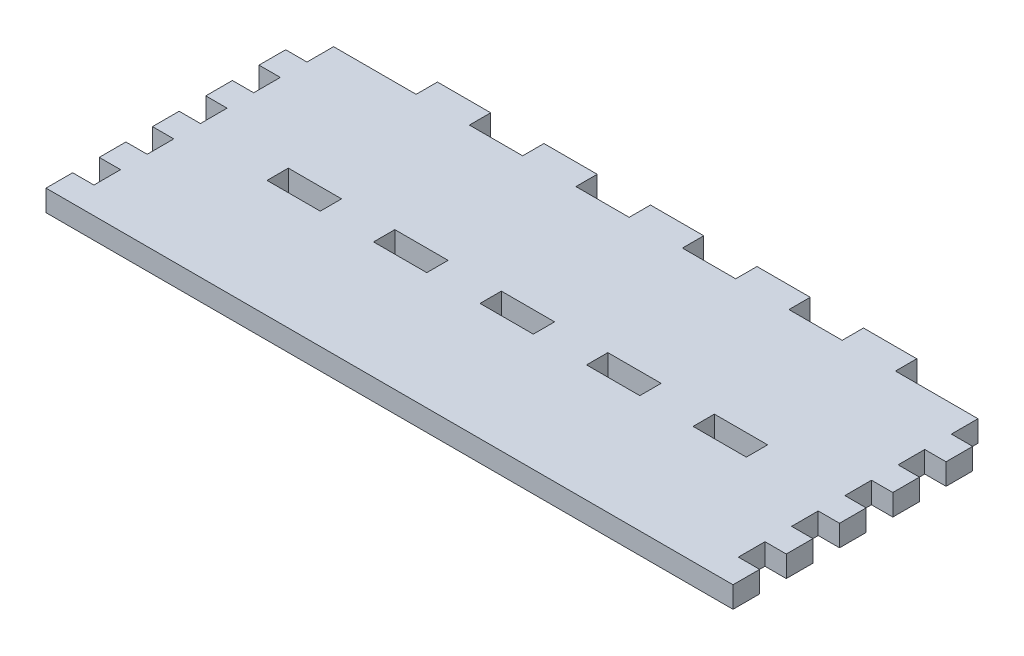
SolidWorks part; units mm, degrees
material "Maple"
ref_plane "Front Plane" through (0, 0, 0) normal (0, 0, 1) x (1, 0, 0)
ref_plane "Top Plane" through (0, 0, 0) normal (0, 1, 0) x (1, 0, 0)
ref_plane "Right Plane" through (0, 0, 0) normal (1, 0, 0) x (0, 0, -1)
sketch "Sketch1" plane through (0, 0, 0) normal (0, 1, 0) x (1, 0, 0)
  line L1 (0, 0) -> (121, 0)
  line L2 (0, 0) -> (0, -50)
  line L3 (0, -50) -> (121, -50)
  line L4 (121, 0) -> (121, -50)
  dimension "D1" = 121
  dimension "D2" = 50
extrude "Boss-Extrude1" add sketch "Sketch1" along normal blind 4
sketch "Sketch2" plane through (0, 0, 0) normal (0, -1, 0) x (-1, 0, 0)
  line L0 (0, 0) -> (0, -50) construction
  line L1 (0, -50) -> (4, -50)
  line L2 (0, -50) -> (0, -45)
  line L3 (0, -45) -> (4, -45)
  line L4 (4, -50) -> (4, -45)
  line L5 (-121, -50) -> (-125, -50)
  line L6 (-121, -50) -> (-121, -45)
  line L7 (-121, -45) -> (-125, -45)
  line L8 (-125, -50) -> (-125, -45)
  line L9 (0, -50) -> (-121, -50) construction
  dimension "D1" = 4
  dimension "D2" = 5
extrude "Boss-Extrude2" add sketch "Sketch2" against normal through all
pattern_linear "LPattern1" count 5 spacing 10 along (0, 0, -1) of "Boss-Extrude2"
sketch "Sketch3" plane through (0, 0, 0) normal (0, -1, 0) x (-1, 0, 0)
  line L0 (-60.5, -50) -> (-60.5, 0) construction
  line L1 (4, -50) -> (-125, -50) construction
  line L2 (-121, 0) -> (0, 0) construction
  line L4 (-55.5, 4) -> (-65.5, 4)
  line L5 (-55.5, 4) -> (-55.5, 0)
  line L6 (-55.5, 0) -> (-65.5, 0)
  line L7 (-65.5, 4) -> (-65.5, 0)
  line L8 (-55.5, 4) -> (-65.5, 0) construction
  line L9 (-55.5, 0) -> (-65.5, 4) construction
  point P6 (-60.5, 2)
  dimension "D1" = 4
  dimension "D2" = 10
extrude "Boss-Extrude3" add sketch "Sketch3" against normal through all
pattern_linear "LPattern2" count 3 spacing 20 along (1, 0, 0) count 3 spacing 20 along (-1, 0, 0) of "Boss-Extrude3"
sketch "Sketch4" plane through (0, 0, 0) normal (0, -1, 0) x (1, 0, 0)
  line L1 (15.5, 28) -> (25.5, 28)
  line L2 (15.5, 28) -> (15.5, 24)
  line L3 (15.5, 24) -> (25.5, 24)
  line L4 (25.5, 28) -> (25.5, 24)
  line L5 (35.5, 28) -> (45.5, 28)
  line L6 (35.5, 28) -> (35.5, 24)
  line L7 (35.5, 24) -> (45.5, 24)
  line L8 (45.5, 28) -> (45.5, 24)
  line L9 (55.5, 28) -> (65.5, 28)
  line L10 (55.5, 28) -> (55.5, 24)
  line L11 (55.5, 24) -> (65.5, 24)
  line L12 (65.5, 28) -> (65.5, 24)
  line L13 (75.5, 28) -> (85.5, 28)
  line L14 (75.5, 28) -> (75.5, 24)
  line L15 (75.5, 24) -> (85.5, 24)
  line L16 (85.5, 28) -> (85.5, 24)
  line L17 (95.5, 28) -> (105.5, 28)
  line L18 (95.5, 28) -> (95.5, 24)
  line L19 (95.5, 24) -> (105.5, 24)
  line L20 (105.5, 28) -> (105.5, 24)
extrude "Cut-Extrude1" cut sketch "Sketch4" against normal through all
sketch "Sketch5" [suppressed] plane through (0, 4, 0) normal (0, 1, 0) x (1, 0, 0)
  line L0 (60.5, -50) -> (60.5, 4) construction
  line L1 (-4, -50) -> (125, -50) construction
  line L2 (55.5, 4) -> (65.5, 4) construction
  line L3 (121, -35) -> (121, -30) construction
  line L4 (54.5, -28) -> (66.5, -28)
  line L5 (54.5, -28) -> (54.5, -36)
  line L6 (54.5, -36) -> (66.5, -36)
  line L7 (66.5, -28) -> (66.5, -36)
  line L8 (54.5, -28) -> (66.5, -36) construction
  line L9 (54.5, -36) -> (66.5, -28) construction
  line L10 (0, -30) -> (0, -35) construction
  line L11 (105.5, -28) -> (95.5, -28) construction
  circle A0 centre (97.5, -33) radius 1.5
  circle A1 centre (102.5, -33) radius 1.5
  circle A2 centre (43, -33) radius 1.5
  circle A3 centre (38, -33) radius 1.5
  circle A4 centre (33, -33) radius 1.5
  circle A5 centre (28, -33) radius 1.5
  circle A6 centre (23, -33) radius 1.5
  circle A7 centre (18, -33) radius 1.5
  point P6 (60.5, -32)
  dimension "D4" = 3
  dimension "D5" = 3
  dimension "D1" = 8
  dimension "D2" = 12
  dimension "D3" = 18
  dimension "D6" = 5
  dimension "D8" = 18.5
  dimension "D9" = 5
  dimension "D10" = 5
  dimension "D11" = 5
  dimension "D12" = 5
  dimension "D13" = 5
  dimension "D14" = 18
  dimension "D7" = 5
extrude "Cut-Extrude2" [suppressed] cut sketch "Sketch5" against normal through all
equation "\"D5@Sketch5\"=\"D4@Sketch5\""
equation "\"D10@Sketch5\"=\"D9@Sketch5\""
equation "\"D11@Sketch5\"=\"D9@Sketch5\""
equation "\"D12@Sketch5\"=\"D9@Sketch5\""
equation "\"D13@Sketch5\"=\"D9@Sketch5\""
